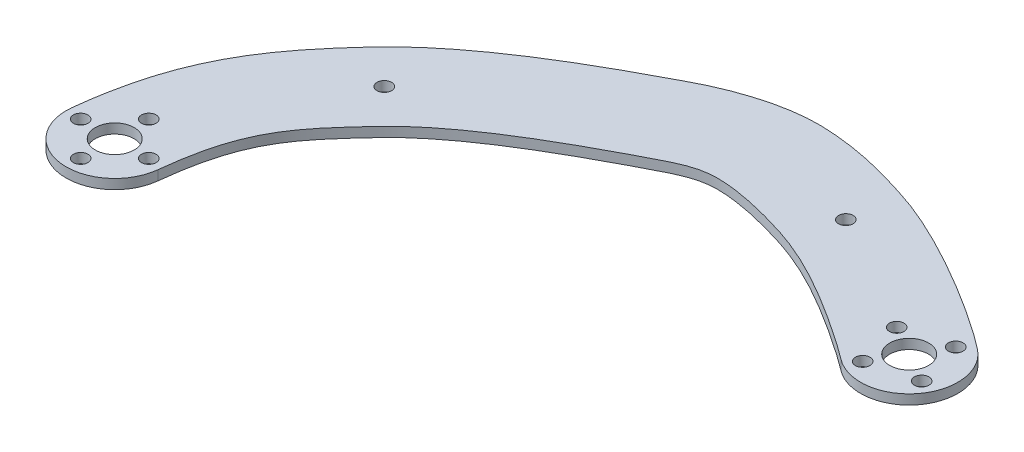
SolidWorks part; units mm, degrees
material "1060 Alloy"
ref_plane "Front Plane" through (0, 0, 0) normal (0, 0, 1) x (1, 0, 0)
ref_plane "Top Plane" through (0, 0, 0) normal (0, 1, 0) x (1, 0, 0)
ref_plane "Right Plane" through (0, 0, 0) normal (1, 0, 0) x (0, 0, -1)
sketch "Sketch1" plane through (0, 0, 0) normal (0, 1, 0) x (1, 0, 0)
  arc A0 (-104.94, 1.0939) -> (-85.06, -1.0939) centre (-95, 0) ccw
  arc A1 (18.782, 35.4695) -> (31.218, 51.1331) centre (25, 43.3013) ccw
  spline S0 degree 3 poles (31.218, 51.1331) (25.2015, 55.9098) (8.3445, 66.7804) (-9.9545, 72.7369) (-16.0662, 74.5136) (-31.4946, 75.2497) (-39.7481, 72.4528) (-57.9892, 62.9083) (-74.5149, 54.009) (-95.3612, 31.4574) (-102.7216, 21.2524) (-104.94, 1.0939) knots 0 0 0 0 0.25 0.25 0.375 0.375 0.5 0.5 0.75 0.75 1 1 1 1
  spline S1 degree 3 poles (-85.06, -1.0939) (-83.2734, 15.1409) (-78.4954, 20.2491) (-62.0102, 38.0642) (-47.28, 45.9574) (-31.2343, 54.3259) (-28.951, 55.1128) (-20.5535, 54.7013) (-14.7921, 53.2658) (-5.2284, 50.1741) (-0.1972, 47.7617) (11.5843, 40.6634) (17.4219, 36.5494) (18.782, 35.4695) knots 0 0 0 0 0.25 0.25 0.5 0.5 0.625 0.625 0.75 0.75 0.875 0.875 1 1 1 1
extrude "Boss-Extrude1" add sketch "Sketch1" against normal blind 2
hole_wizard "Ø8.0 (8) Diameter Hole1" positions "Sketch3" profile "Sketch2" hole size "Ø8.0" standard "ANSI Metric"
sketch "Sketch3" plane through (0, 0, 0) normal (0, 1, 0) x (1, 0, 0)
  point P0 (-95, 0)
  point P1 (25, 43.3013)
sketch "Sketch2" plane through (-95, 0, 0) normal (1, 0, 0) x (0, 0, 1)
  line L0 (0, 0) -> (0, 2)
  line L1 (0, 2) -> (4, 2)
  line L2 (4, 2) -> (4, 0)
  line L5 (4, 0) -> (0, 0)
  line L11 (0, -6.35) -> (0, 107.95) construction
  dimension "Thru Hole Dia." = 8
  dimension "Thru Hole Depth" = 2
hole_wizard "Ø3.0 (3) Diameter Hole1" positions "Sketch5" profile "Sketch4" hole size "Ø3.0" standard "ANSI Metric"
sketch "Sketch5" plane through (0, 0, 0) normal (0, 1, 0) x (1, 0, 0)
  point P0 (-76.5974, 37.0062)
  point P1 (-5.4704, 60.7459)
  point P2 (31.0622, 39.8013)
  point P3 (-88, 0)
  point P4 (-102, 0)
  point P5 (21.5, 37.2391)
  point P6 (28.5, 49.3634)
  point P7 (-95, 7)
  point P8 (-95, -7)
  point P9 (18.9378, 46.8013)
sketch "Sketch4" plane through (-76.5974, 0, -37.0062) normal (1, 0, 0) x (0, 0, 1)
  line L0 (0, 0) -> (0, 2)
  line L1 (0, 2) -> (1.5, 2)
  line L2 (1.5, 2) -> (1.5, 0)
  line L5 (1.5, 0) -> (0, 0)
  line L11 (0, -6.35) -> (0, 107.95) construction
  dimension "Thru Hole Dia." = 3
  dimension "Thru Hole Depth" = 2
chamfer "Chamfer1" [suppressed] distance 0.5 angle 45
chamfer "Chamfer2" [suppressed] distance 0.5 angle 45
